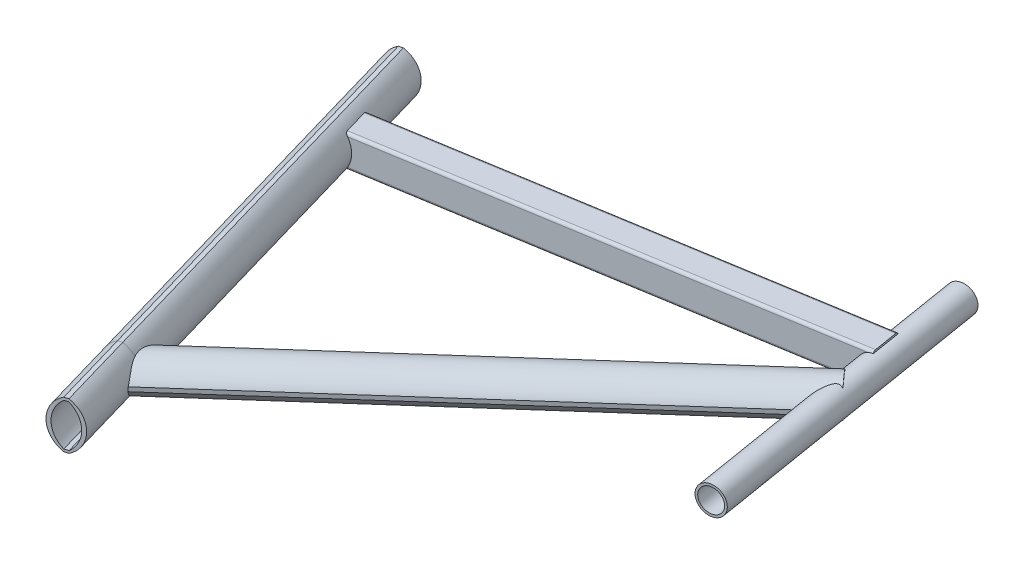
SolidWorks part; units mm, degrees
material "6061 Alloy"
ref_plane "Front Plane" through (0, 0, 0) normal (0, 0, 1) x (1, 0, 0)
ref_plane "Top Plane" through (0, 0, 0) normal (0, 1, 0) x (1, 0, 0)
ref_plane "Right Plane" through (0, 0, 0) normal (1, 0, 0) x (0, 0, -1)
sketch "Sketch1" plane through (0, 0, 0) normal (0, 1, 0) x (1, 0, 0)
  line L0 (50.1987, -91.723) -> (-72.1138, 329.9871)
  line L1 (-46.9762, 243.3176) -> (451.3673, 325.0412)
  line L2 (435.437, 422.1825) -> (487.883, 102.3713)
  line L3 (460.098, 271.8023) -> (50.1987, -91.723)
  line L4 (50.1987, -91.723) -> (73.6306, -172.5118)
  dimension "D1" = 505
  dimension "D2" = 346.35
  dimension "D3" = 53.95
ref_plane "Plane1" through (50.1987, 0, 91.723) normal (-0.2786, 0, -0.9604) x (-0.9604, 0, 0.2786)
ref_plane "Plane2" through (50.1987, 0, 91.723) normal (-0.2786, 0, -0.9604) x (-0.9604, 0, 0.2786)
ref_plane "Plane3" through (50.1987, 0, 91.723) normal (-0.2786, 0, -0.9604) x (-0.9604, 0, 0.2786)
ref_plane "Plane4" through (50.1987, 0, 91.723) normal (-0.2786, 0, -0.9604) x (-0.9604, 0, 0.2786)
ref_plane "Plane5" through (50.1987, 0, 91.723) normal (-0.2786, 0, -0.9604) x (-0.9604, 0, 0.2786)
ref_plane "Plane6" through (50.1987, 0, 91.723) normal (-0.2786, 0, -0.9604) x (-0.9604, 0, 0.2786)
other "Back frame BACK FRAME(1)"
ref_plane "Plane8" through (50.1987, 0, 91.723) normal (-0.2786, 0, -0.9604) x (-0.9604, 0, 0.2786)
sketch "Sketch12" plane through (50.1987, 0, 91.723) normal (-0.2786, 0, -0.9604) x (-0.9604, 0, 0.2786)
  circle A0 centre (0, 0) radius 15
  circle A1 centre (0, 0) radius 12.5
  point P4 (0, 0)
  dimension "D1" = 30
  dimension "D2" = 25
other "Back frame BACK FRAME(2)"
ref_plane "Plane9" through (435.437, 0, -422.1825) normal (0.1618, 0, 0.9868) x (0.9868, 0, -0.1618)
sketch "Sketch13" plane through (435.437, 0, -422.1825) normal (0.1618, 0, 0.9868) x (0.9868, 0, -0.1618)
  circle A0 centre (0, 0) radius 15
  circle A1 centre (0, 0) radius 12.5
  point P4 (0, 0)
  dimension "D1" = 30
  dimension "D2" = 25
other "Top frame TOP TUBE(1)"
ref_plane "Plane10" through (-46.9762, 0, -243.3176) normal (0.9868, 0, -0.1618) x (0, 1, 0)
sketch "Sketch14" plane through (-46.9762, 0, -243.3176) normal (0.9868, 0, -0.1618) x (0, 1, 0)
  line L1 (-14.05, 16.15) -> (14.05, 16.15)
  line L2 (-17.05, 13.15) -> (-17.05, -13.15)
  line L3 (-14.05, -16.15) -> (14.05, -16.15)
  line L4 (17.05, 13.15) -> (17.05, -13.15)
  line L5 (-17.05, 16.15) -> (17.05, -16.15) construction
  line L6 (-17.05, -16.15) -> (17.05, 16.15) construction
  line L7 (-9.5, 11.8402) -> (9.5, 11.8402)
  line L8 (-12.5, 8.8402) -> (-12.5, -8.8402)
  line L9 (-9.5, -11.8402) -> (9.5, -11.8402)
  line L10 (12.5, 8.8402) -> (12.5, -8.8402)
  line L11 (-12.5, 11.8402) -> (12.5, -11.8402) construction
  line L12 (-12.5, -11.8402) -> (12.5, 11.8402) construction
  arc A0 (9.5, -11.8402) -> (12.5, -8.8402) centre (9.5, -8.8402) ccw
  arc A1 (9.5, 11.8402) -> (12.5, 8.8402) centre (9.5, 8.8402) cw
  arc A2 (-9.5, 11.8402) -> (-12.5, 8.8402) centre (-9.5, 8.8402) ccw
  arc A3 (-12.5, -8.8402) -> (-9.5, -11.8402) centre (-9.5, -8.8402) ccw
  arc A4 (-17.05, -13.15) -> (-14.05, -16.15) centre (-14.05, -13.15) ccw
  arc A5 (14.05, -16.15) -> (17.05, -13.15) centre (14.05, -13.15) ccw
  arc A6 (14.05, 16.15) -> (17.05, 13.15) centre (14.05, 13.15) cw
  arc A7 (-14.05, 16.15) -> (-17.05, 13.15) centre (-14.05, 13.15) ccw
  point P0 (0, 0)
  point P6 (0, 0)
  point P35 (0, 0)
  dimension "D4" = 3
  dimension "D1" = 34.1
  dimension "D2" = 25
  dimension "D3" = 32.3
other "Lower frame BOTTOM FRAME(1)"
ref_plane "Plane11" through (460.098, 0, -271.8023) normal (-0.7482, 0, 0.6635) x (0, 1, 0)
sketch "Sketch17" plane through (460.098, 0, -271.8023) normal (-0.7482, 0, 0.6635) x (0, 1, 0)
  line L0 (1.0396, 22.3299) -> (-0.9604, 22.3299)
  line L1 (1.125, 25.2) -> (-1.125, 25.2)
  line L3 (1.125, -25.2) -> (-1.125, -25.2)
  line L5 (1.0396, -22.6701) -> (-1.2104, -22.6701)
  line L6 (-3.4604, -22.6701) -> (-1.2104, -22.6701)
  line L7 (-3.375, -25.2) -> (-1.125, -25.2)
  line L8 (-3.375, 25.2) -> (-1.125, 25.2)
  line L9 (-3.2104, 22.3299) -> (-0.9604, 22.3299)
  arc A0 (1.125, 25.2) -> (1.125, -25.2) centre (-12.071, 0) cw
  arc A1 (-3.375, 25.2) -> (-3.375, -25.2) centre (9.821, 0) ccw
  arc A2 (1.0396, 22.3299) -> (1.0396, -22.6701) centre (-16.3651, -0.1701) cw
  arc A3 (-3.2104, 22.3299) -> (-3.4604, -22.6701) centre (14.0686, -0.2668) ccw
  point P0 (0, 0)
  point P7 (0, 0)
  point P8 (-0.0854, 2.5299)
  dimension "D4" = 2
  dimension "D1" = 50.4
  dimension "D2" = 2.25
  dimension "D3" = 45
other "Lower frame BOTTOM FRAME(2)"
ref_plane "Plane12" through (50.1987, 0, 91.723) normal (-0.2786, 0, -0.9604) x (-0.9604, 0, 0.2786)
sketch "Sketch18" plane through (50.1987, 0, 91.723) normal (-0.2786, 0, -0.9604) x (-0.9604, 0, 0.2786)
  line L0 (1.0396, 22.3299) -> (-0.9604, 22.3299)
  line L1 (1.125, 25.2) -> (-1.125, 25.2)
  line L3 (1.125, -25.2) -> (-1.125, -25.2)
  line L5 (1.0396, -22.6701) -> (-1.2104, -22.6701)
  line L6 (-3.4604, -22.6701) -> (-1.2104, -22.6701)
  line L7 (-3.375, -25.2) -> (-1.125, -25.2)
  line L8 (-3.375, 25.2) -> (-1.125, 25.2)
  line L9 (-3.2104, 22.3299) -> (-0.9604, 22.3299)
  arc A0 (1.125, 25.2) -> (1.125, -25.2) centre (-12.071, 0) cw
  arc A1 (-3.375, 25.2) -> (-3.375, -25.2) centre (9.821, 0) ccw
  arc A2 (1.0396, 22.3299) -> (1.0396, -22.6701) centre (-16.3651, -0.1701) cw
  arc A3 (-3.2104, 22.3299) -> (-3.4604, -22.6701) centre (14.0686, -0.2668) ccw
  point P0 (0, 0)
  point P7 (0, 0)
  point P8 (-0.0854, 2.5299)
  dimension "D4" = 2
  dimension "D1" = 50.4
  dimension "D2" = 2.25
  dimension "D3" = 45
